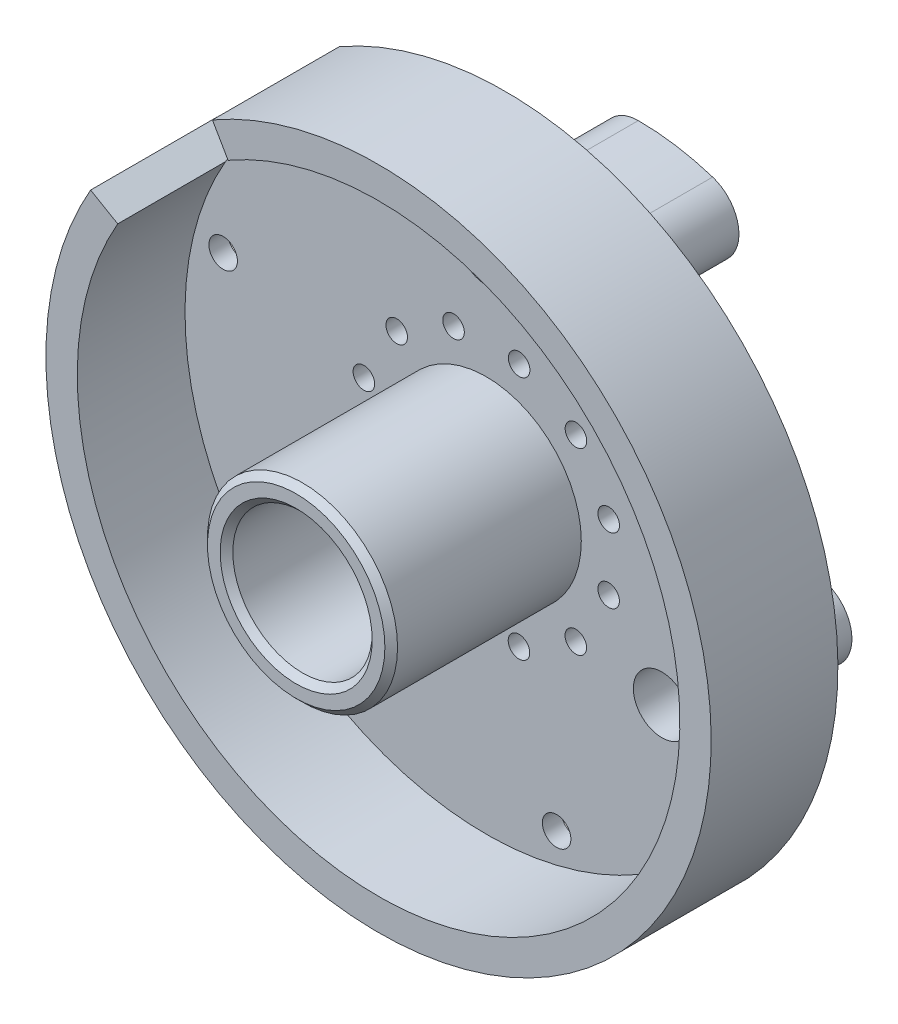
SolidWorks part; units mm, degrees
ref_plane "前视基准面" through (0, 0, 0) normal (0, 0, 1) x (1, 0, 0)
ref_plane "上视基准面" through (0, 0, 0) normal (0, 1, 0) x (1, 0, 0)
ref_plane "右视基准面" through (0, 0, 0) normal (1, 0, 0) x (0, 0, -1)
other "Configuration Table"
sketch "草图1" plane through (0, 0, 0) normal (0, 0, 1) x (1, 0, 0)
  circle A0 centre (0, 0) radius 41
  dimension "D1" = 82
extrude "凸台-拉伸1" add sketch "草图1" along normal blind 6
sketch "草图2" plane through (0, 0, 6) normal (0, 0, 1) x (1, 0, 0)
  circle A0 centre (0, 0) radius 15
  dimension "D1" = 30
extrude "凸台-拉伸2" add sketch "草图2" along normal blind 30
sketch "草图3" plane through (0, 0, 0) normal (0, 0, -1) x (-1, 0, 0)
  circle A0 centre (0, 0) radius 9.275
  dimension "D1" = 18.55
extrude "切除-拉伸2" cut sketch "草图3" against normal blind 7
sketch "草图6" plane through (0, 0, 7) normal (0, 0, -1) x (-1, 0, 0)
  circle A0 centre (0, 0) radius 11
  dimension "D1" = 22
extrude "切除-拉伸3" cut sketch "草图6" against normal through all
chamfer "倒角1" distance 0.5 angle 45 1 edges at (-9.275, 0, 0)
sketch "草图7" plane through (0, 0, 0) normal (0, 0, -1) x (-1, 0, 0)
  line L0 (0, 3.3) -> (0, -3.3) construction
  circle A0 centre (0, 32) radius 6
  dimension "D1" = 12
  dimension "D2" = 32
extrude "凸台-拉伸3" add sketch "草图7" along normal blind 18
pattern_circular "阵列(圆周)1" count 3 over 360 about axis through (0, 0, 0) along (0, 0, 1) of "凸台-拉伸3"
sketch "草图8" plane through (0, 0, 6) normal (0, 0, 1) x (1, 0, 0)
  line L0 (0, -3.3) -> (0, 3.3) construction
  circle A0 centre (0, 32) radius 4.5
  dimension "D1" = 9
  dimension "D2" = 32
extrude "切除-拉伸4" cut sketch "草图8" against normal blind 17
pattern_circular "阵列(圆周)2" count 3 over 360 about axis through (0, 0, 0) along (0, 0, 1) of "切除-拉伸4"
sketch "草图9" plane through (0, 0, -11) normal (0, 0, 1) x (1, 0, 0)
  circle A0 centre (0, 32) radius 2.25
  dimension "D1" = 4.5
extrude "切除-拉伸5" cut sketch "草图9" against normal through all contours A0
pattern_circular "阵列(圆周)3" count 3 over 360 about axis through (0, 0, 0) along (0, 0, 1) of "切除-拉伸5"
hole_wizard "Ø5.0mm 暗销孔1" positions "草图10" profile "草图11" hole size "Ø5.0" standard "GB" end condition through all
sketch "草图10" plane through (0, 0, 6) normal (0, 0, 1) x (1, 0, 0)
  circle A0 centre (0, 0) radius 32 construction
  point P1 (-21.4211, -23.7726)
  point P5 (-27.7128, -16)
  point P8 (-21.4211, -23.7726)
  point P10 (-21.4211, -23.7726)
  dimension "D1" = 10
sketch "草图11" plane through (-21.4211, -23.7726, 6) normal (1, 0, 0) x (0, -1, 0)
  line L0 (0, 0) -> (0, 24)
  line L1 (0, 24) -> (2.5, 24)
  line L2 (2.5, 24) -> (2.5, 0.025)
  line L3 (2.5, 0.025) -> (2.525, 0)
  line L5 (2.525, 0) -> (0, 0)
  line L6 (-2.5, 0.025) -> (-2.525, 0) construction
  line L11 (0, -6.35) -> (0, 107.95) construction
  dimension "通孔孔直径" = 5
  dimension "通孔孔深度" = 24
  dimension "近端锥形沉头孔直径" = 5.05
  dimension "近端锥形沉头孔角度" = 90
hole_wizard "Ø5.0mm 暗销孔2" positions "草图14" profile "草图15" hole size "Ø5.0" standard "GB" end condition through all
sketch "草图14" plane through (0, 0, 6) normal (0, 0, 1) x (1, 0, 0)
  circle A0 centre (0, 0) radius 32 construction
  point P0 (9.8772, 30.4375)
  dimension "D1" = 10
sketch "草图15" plane through (9.8772, 30.4375, 6) normal (1, 0, 0) x (0, -1, 0)
  line L0 (0, 0) -> (0, 24)
  line L1 (0, 24) -> (2.5, 24)
  line L2 (2.5, 24) -> (2.5, 0.025)
  line L3 (2.5, 0.025) -> (2.525, 0)
  line L5 (2.525, 0) -> (0, 0)
  line L6 (-2.5, 0.025) -> (-2.525, 0) construction
  line L11 (0, -6.35) -> (0, 107.95) construction
  dimension "通孔孔直径" = 5
  dimension "通孔孔深度" = 24
  dimension "近端锥形沉头孔直径" = 5.05
  dimension "近端锥形沉头孔角度" = 90
sketch "草图18" plane through (0, 0, 0) normal (0, 0, -1) x (-1, 0, 0)
  arc A0 (-11.7291, 36.1445) -> (-8.0252, 24.7305) centre (-9.8772, 30.4375) ccw
  arc A1 (-11.7291, 36.1445) -> (0, 38) centre (0, 0) cw
  circle A2 centre (0, 32) radius 6 construction
  arc A3 (-8.0252, 24.7305) -> (0, 26) centre (0, 0) cw
  arc A4 (17.4046, -19.3153) -> (25.4375, -28.23) centre (21.4211, -23.7726) ccw
  arc A5 (25.4375, -28.23) -> (32.909, -19) centre (0, 0) ccw
  circle A6 centre (27.7128, -16) radius 6 construction
  arc A7 (17.4046, -19.3153) -> (22.5167, -13) centre (0, 0) ccw
  arc A8 (0, 38) -> (0, 26) centre (0, 32) ccw
  arc A9 (22.5167, -13) -> (32.909, -19) centre (27.7128, -16) ccw
  dimension "D1" = 12
  dimension "D2" = 12
extrude "凸台-拉伸5" add sketch "草图18" along normal up to surface (18 mm away) up to face at (2.25, 32, -18)
hole_wizard "Ø5.0mm 暗销孔3" positions "3D草图1" profile "草图19" hole size "Ø5.0" standard "GB"
sketch3d "3D草图1"
  line L0 (9.8772, 30.4375, 0) -> (9.8772, 30.4375, 5.975) construction
  line L1 (-21.4211, -23.7726, 0) -> (-21.4211, -23.7726, 5.975) construction
  point P0 (9.8772, 30.4375, 0)
  point P4 (-21.4211, -23.7726, 0)
sketch "草图19" plane through (9.8772, 30.4375, 0) normal (1, 0, 0) x (0, -1, 0)
  line L0 (0, 0) -> (0, 18)
  line L1 (0, 18) -> (2.5, 18)
  line L2 (2.5, 18) -> (2.5, 0.025)
  line L3 (2.5, 0.025) -> (2.525, 0)
  line L5 (2.525, 0) -> (0, 0)
  line L6 (-2.5, 0.025) -> (-2.525, 0) construction
  line L11 (0, -6.35) -> (0, 107.95) construction
  dimension "通孔孔直径" = 5
  dimension "通孔孔深度" = 18
  dimension "近端锥形沉头孔直径" = 5.05
  dimension "近端锥形沉头孔角度" = 90
sketch "草图20" plane through (0, 0, 6) normal (0, 0, 1) x (1, 0, 0)
  circle A0 centre (0, 0) radius 47.55
  circle A1 centre (0, 0) radius 52.5
  dimension "D1" = 105
  dimension "D2" = 95.1
extrude "凸台-拉伸6" add sketch "草图20" against normal blind 3 and the other way blind 17 separate body
sketch "草图23" plane through (0, 0, 23) normal (0, 0, 1) x (1, 0, 0)
  line L0 (0, 0) -> (-53.7031, 53.7771) construction
  line L1 (-52.6418, 54.837) -> (-54.7645, 52.7171) construction
  line L2 (-41.1631, 23.8033) -> (-45.4483, 26.2813)
  line L3 (-23.7467, 41.1958) -> (-26.2187, 45.4844)
  circle A0 centre (0, 0) radius 52.5 construction
  arc A1 (-45.4483, 26.2813) -> (-26.2187, 45.4844) centre (0, 0) cw
  arc A2 (-23.7467, 41.1958) -> (-41.1631, 23.8033) centre (0, 0) ccw
  circle A3 centre (0, 0) radius 47.55 construction
  dimension "D1" = 15
  dimension "D2" = 15
extrude "切除-拉伸6" cut sketch "草图23" against normal through all
sketch "草图25" plane through (0, 0, 6) normal (0, 0, 1) x (1, 0, 0)
  circle A0 centre (0, 0) radius 47.55
  circle A1 centre (0, 0) radius 41
extrude "凸台-拉伸7" add sketch "草图25" against normal blind 3
hole_wizard "M3 六角圆柱头螺钉的柱形沉头孔1" positions "草图26" profile "草图27" counterbore size "M3" standard "GB" end condition through all
sketch "草图26" plane through (0, 0, 0) normal (0, 0, -1) x (-1, 0, 0)
  point P0 (5.1897, -19.315)
sketch "草图27" plane through (-5.1897, -19.315, 0) normal (1, 0, 0) x (0, 1, 0)
  line L0 (0, 0) -> (0, 36)
  line L1 (0, 36) -> (1.7, 36)
  line L3 (1.7, 36) -> (1.7, 3.4)
  line L4 (1.7, 3.4) -> (3, 3.4)
  line L5 (3, 3.4) -> (3, 0)
  line L7 (3, 0) -> (0, 0)
  line L11 (0, -6.35) -> (0, 107.95) construction
  dimension "通孔孔直径" = 3.4
  dimension "通孔孔深度" = 36
  dimension "柱形沉头孔直径" = 6
  dimension "柱形沉头孔深度" = 3.4
pattern_circular "阵列(圆周)4" count 12 over 360 about axis through (0, 0, 0) along (0, 0, 1) of "M3 六角圆柱头螺钉的柱形沉头孔1"
chamfer "倒角2" distance 1 angle 45 2 edges at (15, 0, 36) (-11, 0, 36)
sketch "草图30" plane through (0, 0, 6) normal (0, 0, 1) x (1, 0, 0)
  circle A0 centre (-41.5271, 11.1578) radius 2.25
  dimension "D1" = 4.5
extrude "切除-拉伸9" cut sketch "草图30" against normal through all
pattern_circular "阵列(圆周)16" count 6 over 360 about axis through (0, 0, 0) along (0, 0, 1) of "切除-拉伸9"
sketch "草图31" plane through (0, 0, 3) normal (0, 0, -1) x (-1, 0, 0)
  circle A0 centre (41.5271, 11.1578) radius 4
  dimension "D1" = 8
extrude "切除-拉伸10" cut sketch "草图31" along normal up to surface (3 mm away) up to face at (2.565, -20.8221, 0)
pattern_circular "阵列(圆周)17" count 6 over 360 about axis through (0, 0, 0) along (0, 0, 1) of "切除-拉伸10"
